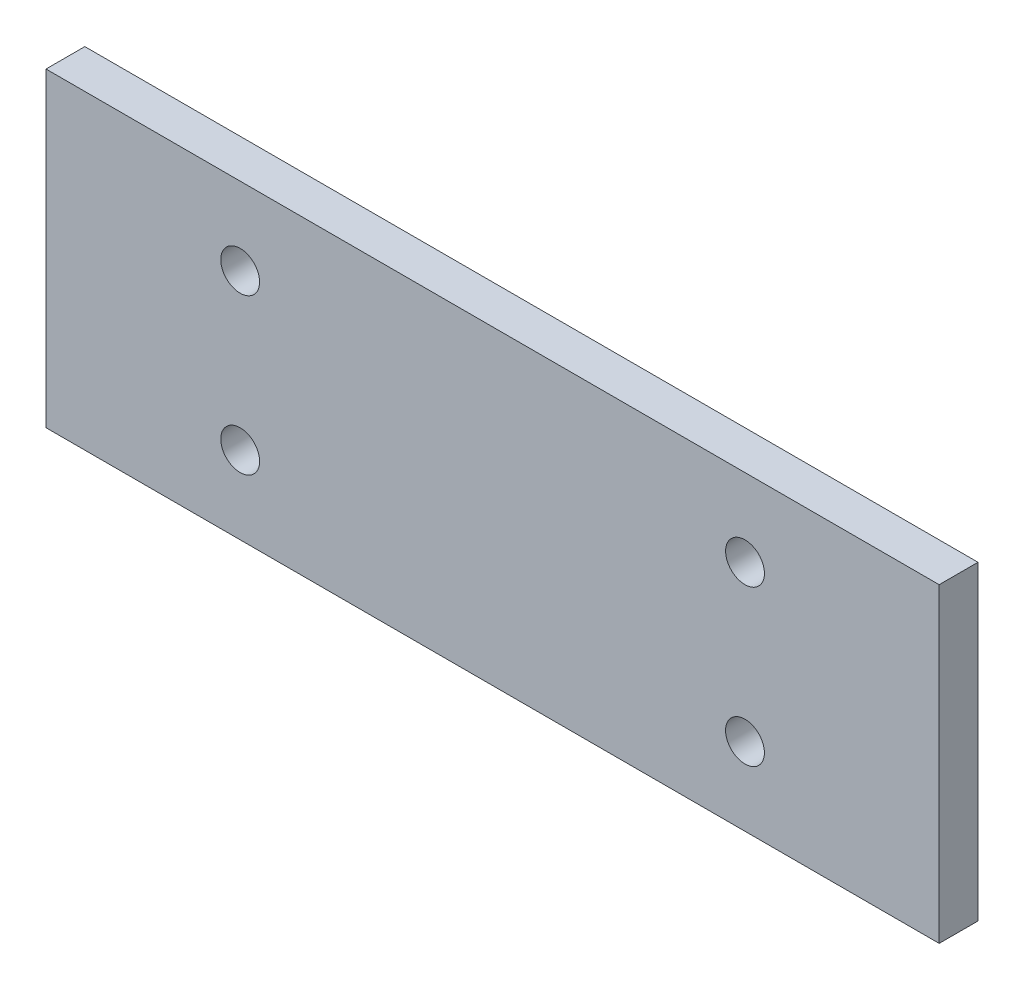
SolidWorks part; units mm, degrees
ref_plane "Front Plane" through (0, 0, 0) normal (0, 0, 1) x (1, 0, 0)
ref_plane "Top Plane" through (0, 0, 0) normal (0, 1, 0) x (1, 0, 0)
ref_plane "Right Plane" through (0, 0, 0) normal (1, 0, 0) x (0, 0, -1)
sketch "Sketch1" plane through (0, 0, 0) normal (0, 0, 1) x (1, 0, 0)
  line L1 (-57.5, 20) -> (57.5, 20)
  line L2 (-57.5, 20) -> (-57.5, -20)
  line L3 (-57.5, -20) -> (57.5, -20)
  line L4 (57.5, 20) -> (57.5, -20)
  line L5 (-57.5, 20) -> (57.5, -20) construction
  line L6 (-57.5, -20) -> (57.5, 20) construction
  point P0 (0, 0)
  dimension "D1" = 115
  dimension "D2" = 40
extrude "Boss-Extrude1" add sketch "Sketch1" along normal blind 5
sketch "Sketch2" plane through (0, 0, 0) normal (0, 0, -1) x (-1, 0, 0)
  line L1 (57.5, -20) -> (-57.5, -20) construction
  line L2 (57.5, 20) -> (57.5, -20) construction
  line L3 (-59.6783, 0) -> (57.5, 0) construction
  circle A0 centre (-32.5, -10) radius 2.5
  circle A1 centre (32.5, -10) radius 2.5
  circle A2 centre (32.5, 10) radius 2.5
  circle A3 centre (-32.5, 10) radius 2.5
  dimension "D6" = 5
  dimension "D2" = 10
  dimension "D3" = 25
  dimension "D4" = 20
  dimension "D5" = 65
  dimension "D1" = 2
extrude "Cut-Extrude1" cut sketch "Sketch2" against normal blind 5
